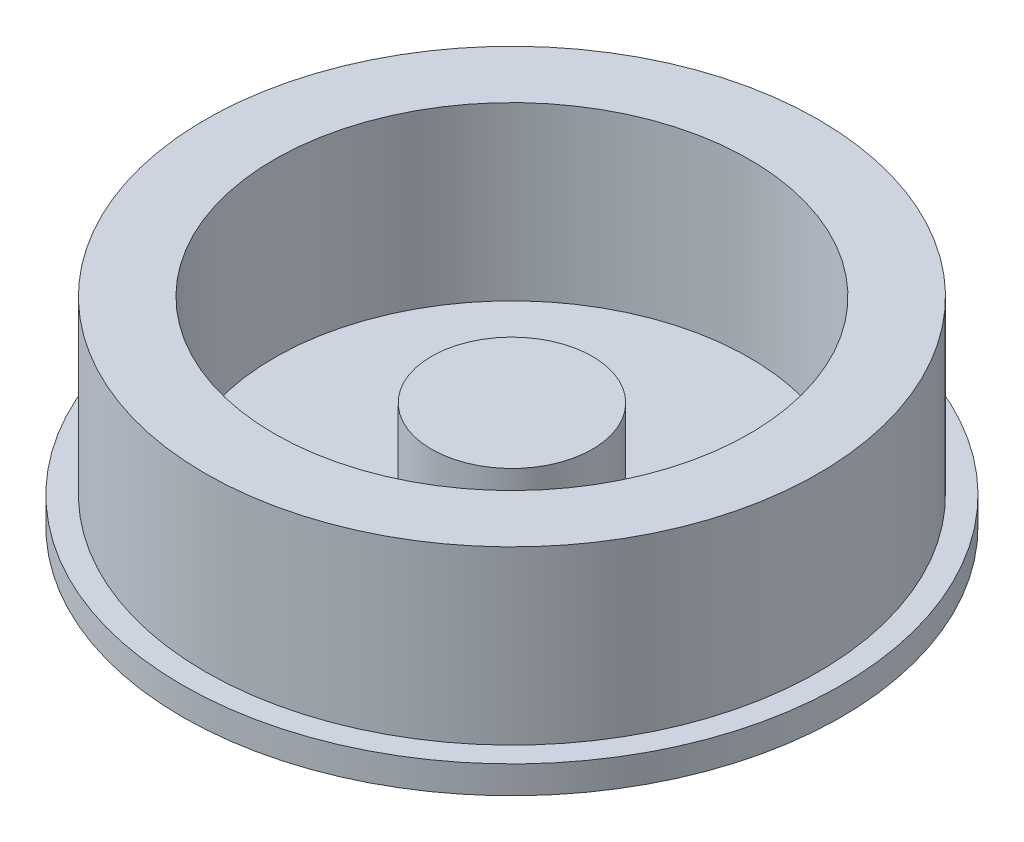
SolidWorks part; units mm, degrees
ref_plane "前视基准面" through (0, 0, 0) normal (0, 0, 1) x (1, 0, 0)
ref_plane "上视基准面" through (0, 0, 0) normal (0, 1, 0) x (1, 0, 0)
ref_plane "右视基准面" through (0, 0, 0) normal (1, 0, 0) x (0, 0, -1)
other "Configuration Table"
sketch "01_Bowl_Flange_Profile" plane through (0, 0, 0) normal (0, 1, 0) x (1, 0, 0)
  circle A0 centre (0, 0) radius 215
  circle A1 centre (170.9177, 70.7964) radius 6
  circle A2 centre (70.7964, 170.9177) radius 6
  circle A3 centre (-70.7964, 170.9177) radius 6
  circle A4 centre (-170.9177, 70.7964) radius 6
  circle A5 centre (-170.9177, -70.7964) radius 6
  circle A6 centre (-70.7964, -170.9177) radius 6
  circle A7 centre (70.7964, -170.9177) radius 6
  circle A8 centre (170.9177, -70.7964) radius 6
extrude "01_Bowl_Base_Flange" add sketch "01_Bowl_Flange_Profile" along normal blind 18
sketch "02_Bowl_Wall_Profile" plane through (0, 0, 0) normal (0, 1, 0) x (1, 0, 0)
  circle A0 centre (0, 0) radius 200
  circle A1 centre (0, 0) radius 155
extrude "02_Bowl_Wall" add sketch "02_Bowl_Wall_Profile" along normal blind 130
sketch "03_Center_Cone_Base" plane through (0, 0, 0) normal (0, 1, 0) x (1, 0, 0)
  circle A0 centre (0, 0) radius 52.5
extrude "03_Center_Guide_Boss" add sketch "03_Center_Cone_Base" along normal blind 70
